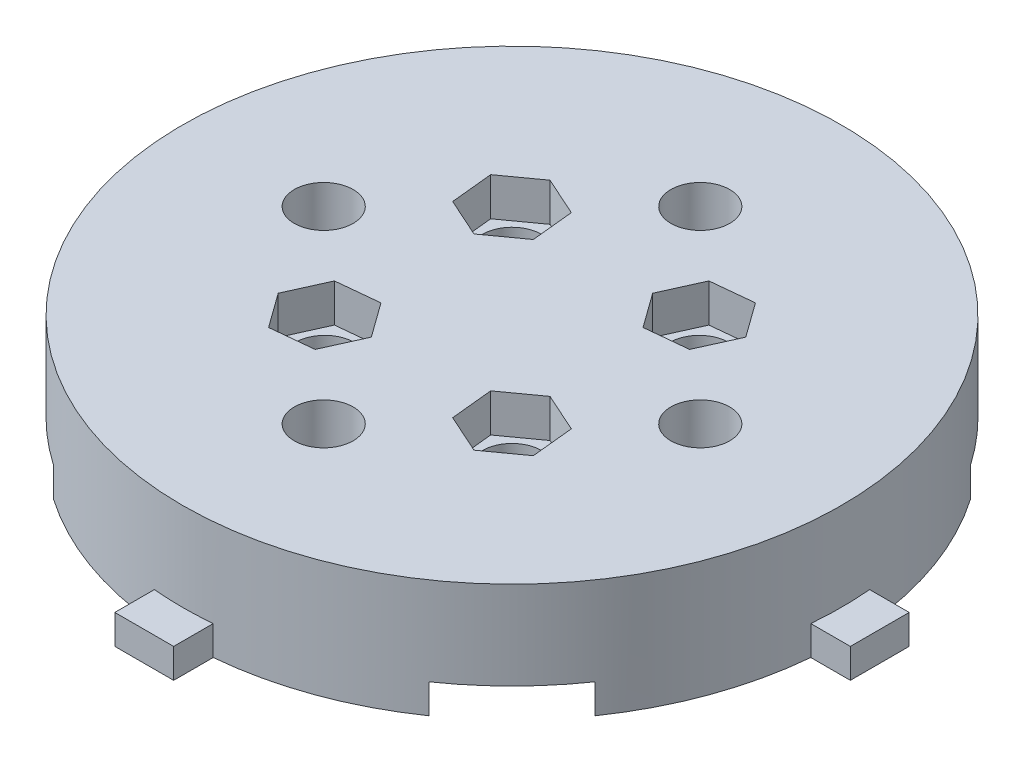
SolidWorks part; units mm, degrees
ref_plane "Front Plane" through (0, 0, 0) normal (0, 0, 1) x (1, 0, 0)
ref_plane "Top Plane" through (0, 0, 0) normal (0, 1, 0) x (1, 0, 0)
ref_plane "Right Plane" through (0, 0, 0) normal (1, 0, 0) x (0, 0, -1)
sketch "Sketch1" plane through (0, 0, 0) normal (0, 1, 0) x (1, 0, 0)
  line L0 (0, 34.8236) -> (0, -34.8236) construction
  line L1 (-15.9099, -15.9099) -> (15.9099, 15.9099) construction
  line L2 (-15.9099, 15.9099) -> (15.9099, -15.9099) construction
  line L3 (-32, 0) -> (47.7968, 0) construction
  circle A0 centre (0, 0) radius 56
  circle A1 centre (15.9099, 15.9099) radius 5
  circle A2 centre (15.9099, -15.9099) radius 5
  circle A3 centre (-15.9099, -15.9099) radius 5
  circle A4 centre (-15.9099, 15.9099) radius 5
  circle A5 centre (-32, 0) radius 5
  circle A6 centre (0, 32) radius 5
  circle A7 centre (32, 0) radius 5
  circle A8 centre (0, -32) radius 5
  point P19 (0, 0)
  point P26 (0, 0)
  dimension "D1" = 112
  dimension "D2" = 10
  dimension "D7" = 10
  dimension "D10" = 10
  dimension "D4" = 22.5
  dimension "D5" = 31.8198
  dimension "D6" = 45
  dimension "D8" = 4
  dimension "D9" = 32
  dimension "D3" = 4
extrude "Boss-Extrude1" add sketch "Sketch1" along normal blind 15 and the other way blind 5
sketch "Sketch3" plane through (0, -5, 0) normal (0, -1, 0) x (1, 0, 0)
  line L0 (-5, 5) -> (-5, 62.5)
  line L1 (5, -62.5) -> (-5, -62.5)
  line L2 (5, -62.5) -> (5, -5)
  line L3 (5, 62.5) -> (-5, 62.5)
  line L4 (-5, -62.5) -> (-5, -5)
  line L5 (5, -62.5) -> (-5, 62.5) construction
  line L6 (5, 62.5) -> (-5, -62.5) construction
  line L7 (62.5, -5) -> (5, -5)
  line L8 (62.5, -5) -> (62.5, 5)
  line L9 (62.5, 5) -> (5, 5)
  line L10 (-62.5, -5) -> (-62.5, 5)
  line L11 (62.5, -5) -> (-62.5, 5) construction
  line L12 (62.5, 5) -> (-62.5, -5) construction
  line L13 (-5, 5) -> (-62.5, 5)
  line L15 (5, 5) -> (5, 62.5)
  line L16 (-5, -5) -> (-62.5, -5)
  point P0 (0, 0)
  point P6 (0, 0)
  dimension "D1" = 125
  dimension "D2" = 125
  dimension "D3" = 10
  dimension "D4" = 10
extrude "Boss-Extrude3" add sketch "Sketch3" against normal blind 5
sketch "Sketch4" plane through (0, -5, 0) normal (0, -1, 0) x (1, 0, 0)
  circle A0 centre (0, 0) radius 50
  dimension "D1" = 100
extrude "Cut-Extrude1" cut sketch "Sketch4" against normal blind 10
sketch "Sketch5" plane through (0, -5, 0) normal (0, -1, 0) x (1, 0, 0)
  line L0 (0, 0) -> (78.838, 78.838) construction
  line L1 (27.5699, 41.7121) -> (31.8905, 46.0326)
  line L2 (41.7121, 27.5699) -> (46.0326, 31.8905)
  line L3 (41.7121, -27.5699) -> (46.0326, -31.8905)
  line L4 (27.5699, -41.7121) -> (31.8905, -46.0326)
  line L5 (-27.5699, -41.7121) -> (-31.8905, -46.0326)
  line L6 (-41.7121, -27.5699) -> (-46.0326, -31.8905)
  line L7 (-41.7121, 27.5699) -> (-46.0326, 31.8905)
  line L8 (-27.5699, 41.7121) -> (-31.8905, 46.0326)
  circle A0 centre (0, 0) radius 50 construction
  arc A1 (55.7763, 5) -> (5, 55.7763) centre (0, 0) ccw construction
  arc A2 (46.0326, 31.8905) -> (31.8905, 46.0326) centre (0, 0) ccw
  arc A3 (41.7121, 27.5699) -> (27.5699, 41.7121) centre (0, 0) ccw
  arc A4 (31.8905, -46.0326) -> (46.0326, -31.8905) centre (0, 0) ccw
  arc A5 (27.5699, -41.7121) -> (41.7121, -27.5699) centre (0, 0) ccw
  arc A6 (-46.0326, -31.8905) -> (-31.8905, -46.0326) centre (0, 0) ccw
  arc A7 (-41.7121, -27.5699) -> (-27.5699, -41.7121) centre (0, 0) ccw
  arc A8 (-31.8905, 46.0326) -> (-46.0326, 31.8905) centre (0, 0) ccw
  arc A9 (-27.5699, 41.7121) -> (-41.7121, 27.5699) centre (0, 0) ccw
  point P27 (0, 0)
  dimension "D1" = 45
  dimension "D2" = 10
  dimension "D3" = 4
extrude "Cut-Extrude2" cut sketch "Sketch5" against normal blind 5
sketch "Sketch8" plane through (0, 15, 0) normal (0, 1, 0) x (1, 0, 0)
  line L9 (-5, 5) -> (-5.5902, 5)
  line L10 (5, -5.5902) -> (-5, -5.5902)
  line L11 (5, -5.5902) -> (5, -5)
  line L12 (5, 5.5902) -> (-5, 5.5902)
  line L13 (-5, -5.5902) -> (-5, -5)
  line L14 (0, 7.5) -> (0, -7.5) construction
  line L24 (-7.5, 0) -> (7.5, 0) construction
  line L25 (5, -5.5902) -> (-5, 5.5902) construction
  line L26 (5, 5.5902) -> (-5, -5.5902) construction
  line L27 (5.5902, -5) -> (5, -5)
  line L28 (5.5902, -5) -> (5.5902, 5)
  line L29 (5.5902, 5) -> (5, 5)
  line L30 (-5.5902, -5) -> (-5.5902, 5)
  line L31 (5.5902, -5) -> (-5.5902, 5) construction
  line L32 (5.5902, 5) -> (-5.5902, -5) construction
  line L33 (-5, 5) -> (-5, 5.5902)
  line L35 (5, 5) -> (5, 5.5902)
  line L36 (-5, -5) -> (-5.5902, -5)
  circle A0 centre (0, 0) radius 7.5 construction
  point P12 (0, 0)
  point P13 (0, 0)
  dimension "D1" = 15
  dimension "D2" = 5
  dimension "D3" = 10
extrude "Cut-Extrude5" cut sketch "Sketch8" along normal blind 2.5 from surface at -10 starting at face at (0, 5, -50)
sketch "Sketch10" plane through (0, 15, 0) normal (0, 1, 0) x (1, 0, 0)
  line L0 (11.6887, 21.7706) -> (8.7238, 15.1845)
  line L1 (-16.6353, 23.096) -> (-22.496, 18.8748)
  line L2 (-22.496, 18.8748) -> (-21.7706, 11.6887)
  line L3 (-21.7706, 11.6887) -> (-15.1845, 8.7238)
  line L4 (-15.1845, 8.7238) -> (-9.3238, 12.945)
  line L5 (-9.3238, 12.945) -> (-10.0492, 20.1312)
  line L6 (-10.0492, 20.1312) -> (-16.6353, 23.096)
  line L7 (23.096, 16.6353) -> (18.8748, 22.496)
  line L8 (18.8748, 22.496) -> (11.6887, 21.7706)
  line L9 (8.7238, 15.1845) -> (12.945, 9.3238)
  line L10 (12.945, 9.3238) -> (20.1312, 10.0492)
  line L11 (20.1312, 10.0492) -> (23.096, 16.6353)
  line L12 (21.7706, -11.6887) -> (15.1845, -8.7238)
  line L13 (16.6353, -23.096) -> (22.496, -18.8748)
  line L14 (22.496, -18.8748) -> (21.7706, -11.6887)
  line L15 (15.1845, -8.7238) -> (9.3238, -12.945)
  line L16 (9.3238, -12.945) -> (10.0492, -20.1312)
  line L17 (10.0492, -20.1312) -> (16.6353, -23.096)
  line L18 (-11.6887, -21.7706) -> (-8.7238, -15.1845)
  line L19 (-23.096, -16.6353) -> (-18.8748, -22.496)
  line L20 (-18.8748, -22.496) -> (-11.6887, -21.7706)
  line L21 (-8.7238, -15.1845) -> (-12.945, -9.3238)
  line L22 (-12.945, -9.3238) -> (-20.1312, -10.0492)
  line L23 (-20.1312, -10.0492) -> (-23.096, -16.6353)
  circle A0 centre (-15.9099, 15.9099) radius 6.255 construction
  circle A1 centre (0, 0) radius 22.5 construction
  point P34 (0, 0)
  dimension "D1" = 12.51
  dimension "D2" = 14.4453
  dimension "D3" = 4
extrude "Cut-Extrude6" cut sketch "Sketch10" against normal blind 6.5
